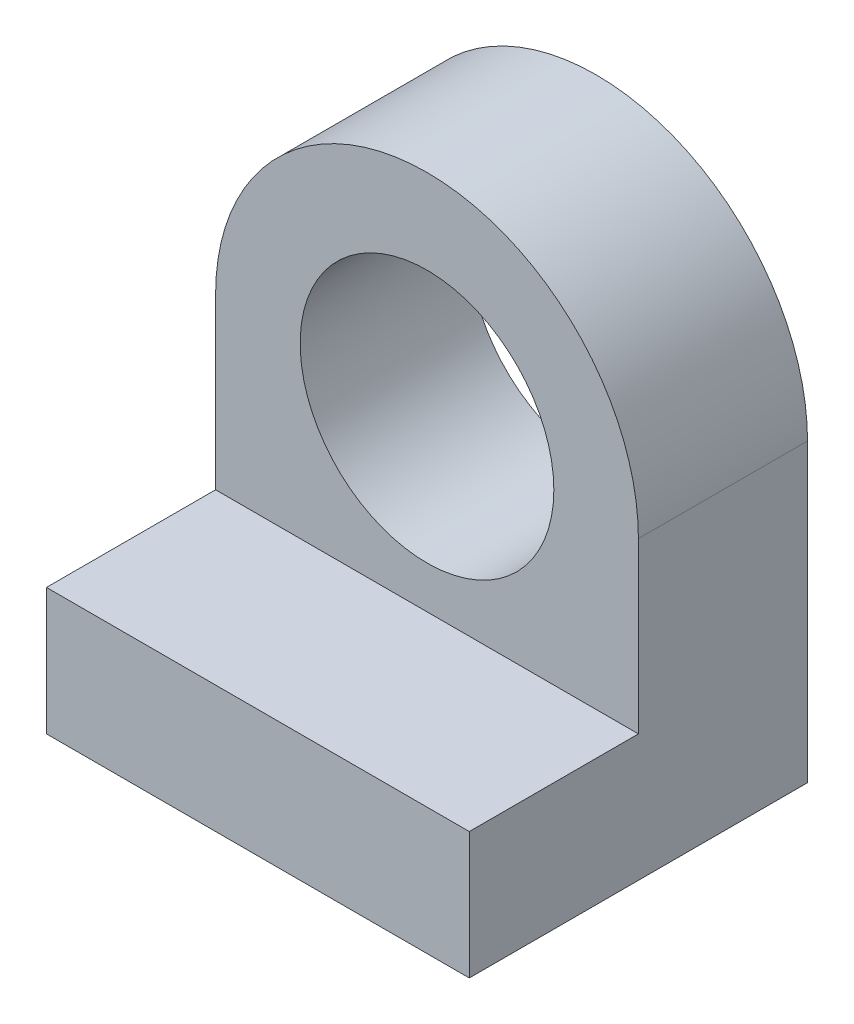
SolidWorks part; units mm, degrees
ref_plane "Alzado" through (0, 0, 0) normal (0, 0, 1) x (1, 0, 0)
ref_plane "Planta" through (0, 0, 0) normal (0, 1, 0) x (1, 0, 0)
ref_plane "Vista lateral" through (0, 0, 0) normal (1, 0, 0) x (0, 0, -1)
sketch "Croquis1" plane through (0, 0, 0) normal (0, 0, 1) x (1, 0, 0)
  line L0 (-12.5, 0) -> (12.5, 0)
  line L1 (-12.5, 0) -> (-12.5, 7.5)
  line L2 (-12.5, 7.5) -> (12.5, 7.5)
  line L3 (12.5, 7.5) -> (12.5, 0)
  point P4 (0, 0)
  dimension "D1" = 25
  dimension "D2" = 7.5
extrude "Saliente-Extruir1" add sketch "Croquis1" against normal blind 20
ref_plane "Plano2" through (0, 0, -10) normal (0, 0, 1) x (1, 0, 0)
sketch "Croquis8" plane through (0, 0, -10) normal (0, 0, 1) x (1, 0, 0)
  line L0 (0, 0) -> (0, 17.5) construction
  line L1 (-12.5, 17.5) -> (-12.5, 7.5)
  line L2 (12.5, 17.5) -> (12.5, 7.5)
  line L3 (12.5, 7.5) -> (-12.5, 7.5) construction
  line L4 (-12.5, 7.5) -> (12.5, 7.5)
  circle A0 centre (0, 17.5) radius 7.5
  arc A1 (12.5, 17.5) -> (-12.5, 17.5) centre (0, 17.5) ccw
  dimension "D2" = 15
  dimension "D3" = 25
  dimension "D1" = 17.5
extrude "Saliente-Extruir6" add sketch "Croquis8" against normal blind 10
